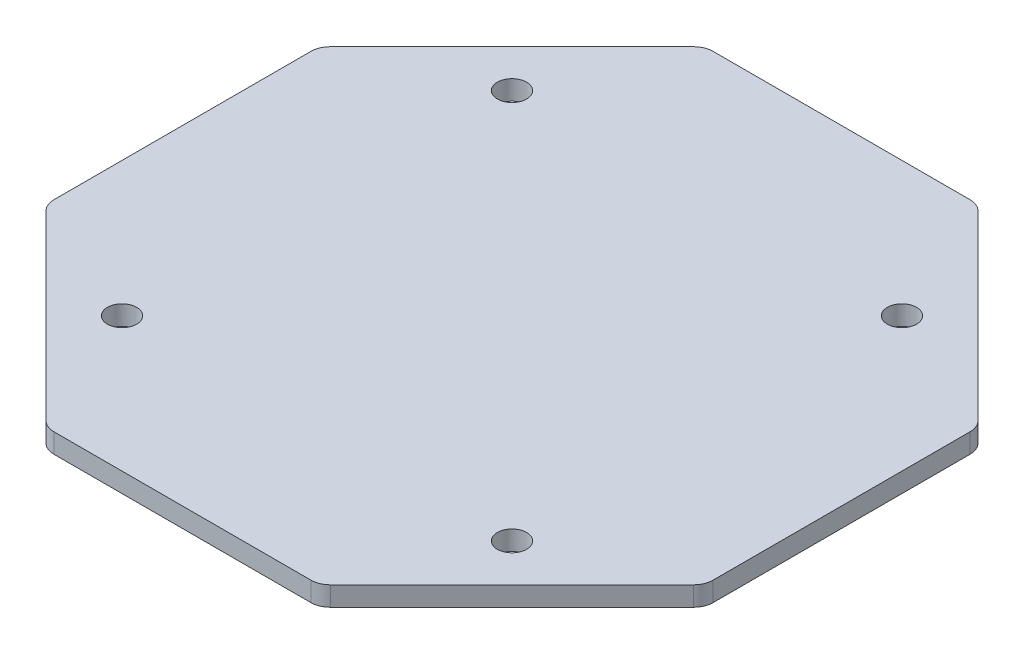
SolidWorks part; units mm, degrees
ref_plane "Front Plane" through (0, 0, 0) normal (0, 0, 1) x (1, 0, 0)
ref_plane "Top Plane" through (0, 0, 0) normal (0, 1, 0) x (1, 0, 0)
ref_plane "Right Plane" through (0, 0, 0) normal (1, 0, 0) x (0, 0, -1)
sketch "Sketch1" plane through (0, 0, 0) normal (0, 1, 0) x (1, 0, 0)
  line L0 (-14, 33.799) -> (14, 33.799)
  line L1 (14, 33.799) -> (33.799, 14)
  line L2 (33.799, 14) -> (33.799, -14)
  line L3 (33.799, -14) -> (14, -33.799)
  line L4 (14, -33.799) -> (-14, -33.799)
  line L5 (-14, -33.799) -> (-33.799, -14)
  line L6 (-33.799, -14) -> (-33.799, 14)
  line L7 (-33.799, 14) -> (-14, 33.799)
  line L8 (0, 33.799) -> (0, -33.799) construction
  point P10 (0, 0)
  dimension "D1" = 28
  dimension "D2" = 45
  dimension "D3" = 45
  dimension "D4" = 67.598
extrude "Boss-Extrude1" add sketch "Sketch1" along normal blind 2
fillet "Fillet1" radius 2 8 edges at (-33.799, 1, 14) (-33.799, 1, -14) (-14, 1, -33.799) (14, 1, -33.799) (33.799, 1, -14) (33.799, 1, 14) (14, 1, 33.799) (-14, 1, 33.799)
sketch "Sketch2" plane through (0, 2, 0) normal (0, 1, 0) x (1, 0, 0)
  line L1 (-20, -20) -> (20, -20) construction
  line L2 (-20, -20) -> (-20, 20) construction
  line L3 (-20, 20) -> (20, 20) construction
  line L4 (20, -20) -> (20, 20) construction
  line L5 (-20, -20) -> (20, 20) construction
  line L6 (-20, 20) -> (20, -20) construction
  circle A0 centre (-20, 20) radius 1.5
  circle A1 centre (20, 20) radius 1.5
  circle A2 centre (20, -20) radius 1.5
  circle A3 centre (-20, -20) radius 1.5
  point P0 (0, 0)
  dimension "D3" = 3
  dimension "D1" = 40
extrude "Cut-Extrude1" cut sketch "Sketch2" against normal blind 10
